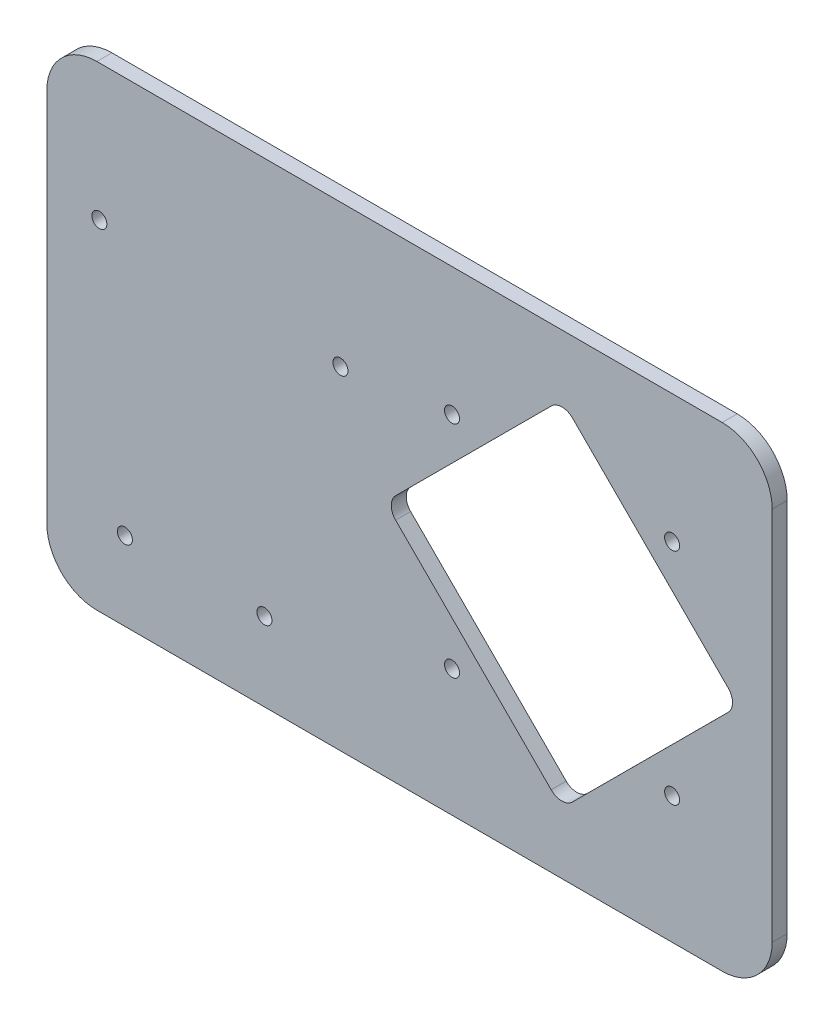
SolidWorks part; units mm, degrees
ref_plane "前视基准面" through (0, 0, 0) normal (0, 0, 1) x (1, 0, 0)
ref_plane "上视基准面" through (0, 0, 0) normal (0, 1, 0) x (1, 0, 0)
ref_plane "右视基准面" through (0, 0, 0) normal (1, 0, 0) x (0, 0, -1)
ref_plane "基准面1" through (0, 0, 0) normal (0, 0, -1) x (-1, 0, 0)
sketch "草图1" plane through (0, 0, 0) normal (0, 0, -1) x (-1, 0, 0)
  line L0 (-109.7196, 49.6555) -> (-78.6256, 80.7866)
  line L1 (-74.383, 80.7891) -> (-43.2517, 49.6949)
  line L2 (-43.2491, 45.4522) -> (-74.3431, 14.3212)
  line L3 (-78.5857, 14.3187) -> (-109.717, 45.4129)
  line L4 (-108.5213, 0) -> (16.4787, 0)
  line L5 (26.4787, 10) -> (26.4787, 84.9993)
  line L6 (16.4787, 94.9993) -> (-108.5213, 94.9993)
  line L7 (-118.5213, 84.9993) -> (-118.5213, 10)
  circle A0 centre (15.9787, 67.8145) radius 1.5
  circle A1 centre (-32.2203, 66.5152) radius 1.5
  circle A2 centre (10.8787, 15.715) radius 1.5
  circle A3 centre (-54.5213, 69.3759) radius 1.5
  circle A4 centre (-98.5203, 69.3759) radius 1.5
  circle A5 centre (-98.5203, 25.3751) radius 1.5
  circle A6 centre (-54.5213, 25.3751) radius 1.5
  circle A7 centre (-17.0213, 15.715) radius 1.5
  arc A8 (-78.6256, 80.7866) -> (-74.383, 80.7891) centre (-76.503, 78.6665) cw
  arc A9 (-43.2517, 49.6949) -> (-43.2491, 45.4522) centre (-45.3717, 47.5723) cw
  arc A10 (-74.3431, 14.3212) -> (-78.5857, 14.3187) centre (-76.4657, 16.4413) cw
  arc A11 (-109.717, 45.4129) -> (-109.7196, 49.6555) centre (-107.597, 47.5355) cw
  arc A12 (16.4787, 0) -> (26.4787, 10) centre (16.4787, 10) ccw
  arc A13 (26.4787, 84.9993) -> (16.4787, 94.9993) centre (16.4787, 84.9993) ccw
  arc A14 (-108.5213, 94.9993) -> (-118.5213, 84.9993) centre (-108.5213, 84.9993) ccw
  arc A15 (-118.5213, 10) -> (-108.5213, 0) centre (-108.5213, 10) ccw
extrude "凸台-拉伸1" add sketch "草图1" against normal blind 3
